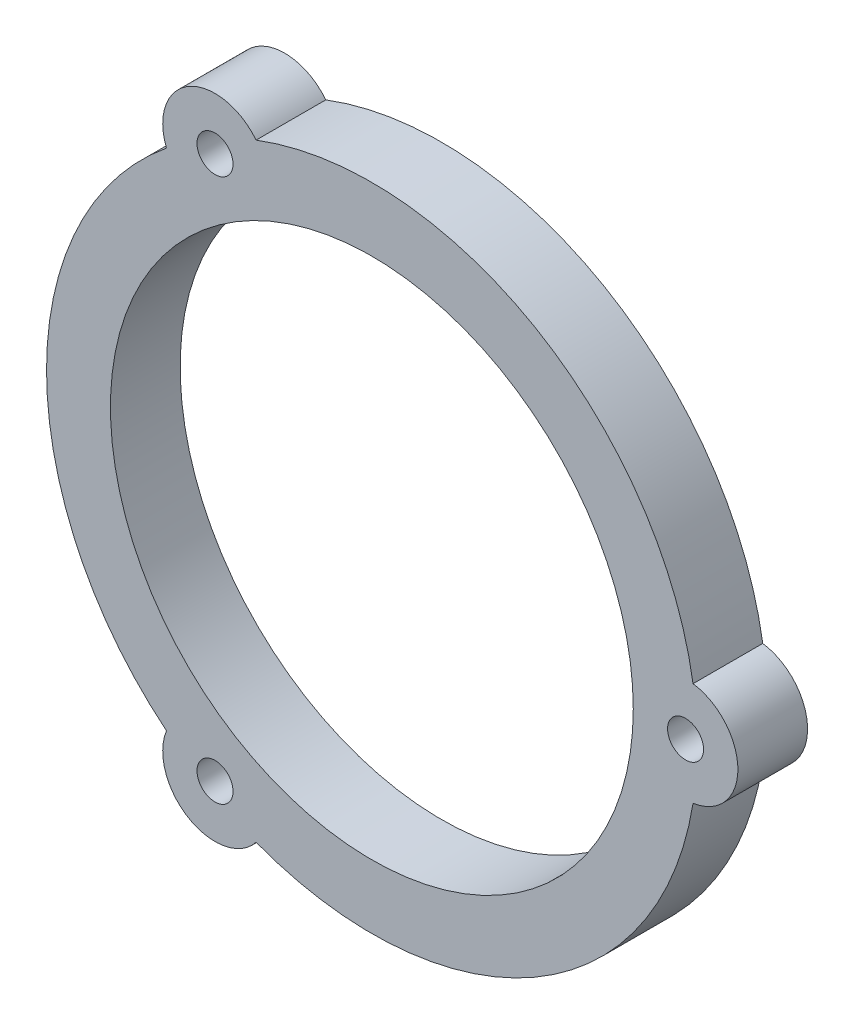
SolidWorks part; units mm, degrees
ref_plane "Płaszczyzna przednia" through (0, 0, 0) normal (0, 0, 1) x (1, 0, 0)
ref_plane "Płaszczyzna górna" through (0, 0, 0) normal (0, 1, 0) x (1, 0, 0)
ref_plane "Płaszczyzna prawa" through (0, 0, 0) normal (1, 0, 0) x (0, 0, -1)
sketch "Szkic1" plane through (0, 0, 0) normal (0, 0, 1) x (1, 0, 0)
  circle A0 centre (51.5219, 19.8521) radius 28
  dimension "D1" = 56
extrude "Dodanie-wyciągnięcie1" add sketch "Szkic1" along normal blind 6
sketch "Szkic2" plane through (0, 0, 6) normal (0, 0, 1) x (1, 0, 0)
  line L0 (79.5219, 19.8521) -> (23.5219, 19.8521) construction
  circle A0 centre (51.5219, 19.8521) radius 28 construction
  point P5 (51.5219, 19.8521)
sketch "Szkic3" plane through (0, 0, 6) normal (0, 0, 1) x (1, 0, 0)
  line L0 (79.5219, 19.8521) -> (23.5219, 19.8521) construction
  circle A0 centre (51.5219, 19.8521) radius 22.5
  dimension "D3" = 45
  dimension "D1" = 0
  dimension "D2" = 0
extrude "Wytnij-wyciągnięcie1" cut sketch "Szkic3" against normal blind 6
sketch "Szkic4" plane through (0, 0, 6) normal (0, 0, 1) x (1, 0, 0)
  circle A0 centre (38.0219, 43.2348) radius 1.55 construction
  circle A1 centre (78.5219, 19.8521) radius 1.55 construction
  circle A2 centre (38.0219, -3.5306) radius 1.55 construction
  circle A3 centre (38.0219, 43.2348) radius 1.55
  circle A4 centre (78.5219, 19.8521) radius 1.55
  circle A5 centre (38.0219, -3.5306) radius 1.55
  circle A6 centre (38.0219, -3.5306) radius 4.5
  circle A7 centre (78.5219, 19.8521) radius 4.5
  circle A8 centre (38.0219, 43.2348) radius 4.5
sketch "Szkic5" plane through (0, 0, 6) normal (0, 0, 1) x (1, 0, 0)
  circle A0 centre (78.5219, 19.8521) radius 4.5 construction
  circle A1 centre (38.0219, -3.5306) radius 4.5 construction
  circle A2 centre (38.0219, 43.2348) radius 4.5 construction
  circle A3 centre (78.5219, 19.8521) radius 4.5
  circle A4 centre (38.0219, -3.5306) radius 4.5
  circle A5 centre (38.0219, 43.2348) radius 4.5
extrude "Dodanie-wyciągnięcie2" add sketch "Szkic5" against normal blind 6
sketch "Szkic6" plane through (0, 0, 6) normal (0, 0, 1) x (1, 0, 0)
  circle A0 centre (78.5219, 19.8521) radius 1.55 construction
  circle A1 centre (38.0219, -3.5306) radius 1.55 construction
  circle A2 centre (38.0219, 43.2348) radius 1.55 construction
  circle A3 centre (78.5219, 19.8521) radius 1.55
  circle A4 centre (38.0219, -3.5306) radius 1.55
  circle A5 centre (38.0219, 43.2348) radius 1.55
extrude "Wytnij-wyciągnięcie2" cut sketch "Szkic6" against normal blind 6
